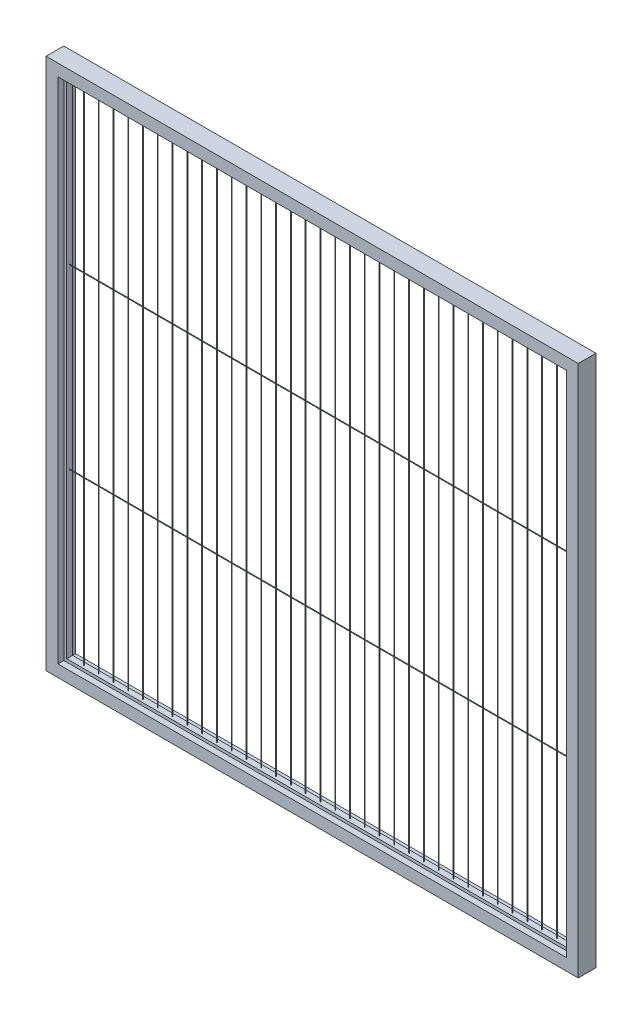
SolidWorks part; units mm, degrees
ref_plane "前视基准面" through (0, 0, 0) normal (0, 0, 1) x (1, 0, 0)
ref_plane "上视基准面" through (0, 0, 0) normal (0, 1, 0) x (1, 0, 0)
ref_plane "右视基准面" through (0, 0, 0) normal (1, 0, 0) x (0, 0, -1)
sketch "草图1" plane through (0, 0, 0) normal (1, 0, 0) x (0, 0, -1)
  line L0 (30, 0) -> (-30, 0)
  line L1 (-30, 0) -> (-30, 40)
  line L2 (-30, 40) -> (-10, 40)
  line L3 (-10, 40) -> (-10, 50)
  line L4 (-10, 50) -> (10, 50)
  line L5 (0, 0) -> (0, 164.1985) construction
  line L6 (10, 40) -> (10, 50)
  line L7 (30, 40) -> (10, 40)
  line L8 (30, 0) -> (30, 40)
  line L9 (-155.4817, 900) -> (236.5603, 900) construction
  line L10 (30, 1800) -> (30, 1760)
  line L11 (30, 1760) -> (10, 1760)
  line L12 (10, 1760) -> (10, 1750)
  line L13 (-10, 1750) -> (10, 1750)
  line L14 (-10, 1760) -> (-10, 1750)
  line L15 (-30, 1760) -> (-10, 1760)
  line L16 (-30, 1800) -> (-30, 1760)
  line L17 (30, 1800) -> (-30, 1800)
  point P9 (0, 50)
  point P22 (0, 1750)
  dimension "D1" = 60
  dimension "D2" = 40
  dimension "D3" = 50
  dimension "D4" = 900
  dimension "D5" = 20
extrude "凸台-拉伸1" add sketch "草图1" along normal mid plane 1800
sketch "草图3" plane through (0, 1760, 0) normal (0, -1, 0) x (1, 0, 0)
  line L0 (-900, -30) -> (-900, 30)
  line L1 (-900, 30) -> (-860, 30)
  line L2 (900, 30) -> (-900, 30) construction
  line L3 (-860, 30) -> (-860, 10)
  line L4 (-860, 10) -> (-850, 10)
  line L5 (-850, 10) -> (-850, -10)
  line L6 (-850, -10) -> (-860, -10)
  line L7 (-860, -10) -> (-860, -30)
  line L8 (900, -30) -> (-900, -30) construction
  line L9 (-860, -30) -> (-900, -30)
  line L10 (-900, 0) -> (-1150.2083, 0) construction
  line L11 (0, 0) -> (0, 199.5388) construction
  line L12 (900, 0) -> (1150.2083, 0) construction
  line L13 (860, -30) -> (900, -30)
  line L14 (860, -10) -> (860, -30)
  line L15 (850, -10) -> (860, -10)
  line L16 (850, 10) -> (850, -10)
  line L17 (860, 10) -> (850, 10)
  line L18 (860, 30) -> (860, 10)
  line L19 (900, 30) -> (860, 30)
  line L20 (900, -30) -> (900, 30)
  dimension "D1" = 40
  dimension "D2" = 50
  dimension "D3" = 20
extrude "凸台-拉伸2" add sketch "草图3" along normal up to surface (1720 mm away) separate body up to face at (0, 40, 20)
sketch "草图4" plane through (0, 1760, 0) normal (0, -1, 0) x (1, 0, 0)
  line L0 (900, -30) -> (-900, -30) construction
  line L1 (-900, 30) -> (-850, 30)
  line L2 (-900, 30) -> (-900, -30)
  line L3 (-900, -30) -> (-850, -30)
  line L4 (-850, 30) -> (-850, -30)
  line L5 (0, 0) -> (0, 218.547) construction
  line L6 (850, 30) -> (850, -30)
  line L7 (900, -30) -> (850, -30)
  line L8 (900, 30) -> (900, -30)
  line L9 (900, 30) -> (850, 30)
  dimension "D1" = 50
extrude "切除-拉伸1" cut sketch "草图4" along normal blind 10
sketch "草图5" plane through (0, 40, 0) normal (0, 1, 0) x (1, 0, 0)
  line L0 (900, -30) -> (-900, -30) construction
  line L1 (-900, 30) -> (-850, 30)
  line L2 (-900, 30) -> (-900, -30)
  line L3 (-900, -30) -> (-850, -30)
  line L4 (-850, 30) -> (-850, -30)
  line L5 (0, 0) -> (0, 304.5992) construction
  line L6 (850, 30) -> (850, -30)
  line L7 (900, -30) -> (850, -30)
  line L8 (900, 30) -> (900, -30)
  line L9 (900, 30) -> (850, 30)
  dimension "50" = 50
extrude "切除-拉伸2" cut sketch "草图5" along normal blind 10
sketch "草图6" plane through (850, 0, 0) normal (-1, 0, 0) x (0, 0, 1)
  line L0 (0, 1800) -> (0, 0) construction
  line L1 (-30, 1800) -> (30, 1800) construction
  circle A0 centre (0, 1200) radius 1
  dimension "D1" = 2
  dimension "D2" = 600
extrude "凸台-拉伸3" add sketch "草图6" along normal up to next (1700 mm away) contours A0
pattern_linear "阵列(线性)1" count 2 spacing 600 along (0, -1, 0) of "凸台-拉伸3"
sketch "草图8" plane through (0, 1750, 0) normal (0, -1, 0) x (1, 0, 0)
  line L0 (-900, 0) -> (900, 0) construction
  line L1 (-900, 30) -> (-900, -30) construction
  line L2 (900, 30) -> (900, -30) construction
  circle A0 centre (-802, 0) radius 1
  dimension "D1" = 2
  dimension "D2" = 98
extrude "凸台-拉伸4" add sketch "草图8" along normal up to surface (1700 mm away) up to face at (0, 50, 0)
pattern_linear "阵列(线性)2" count 48 spacing 50 along (1, 0, 0) of "凸台-拉伸4"
